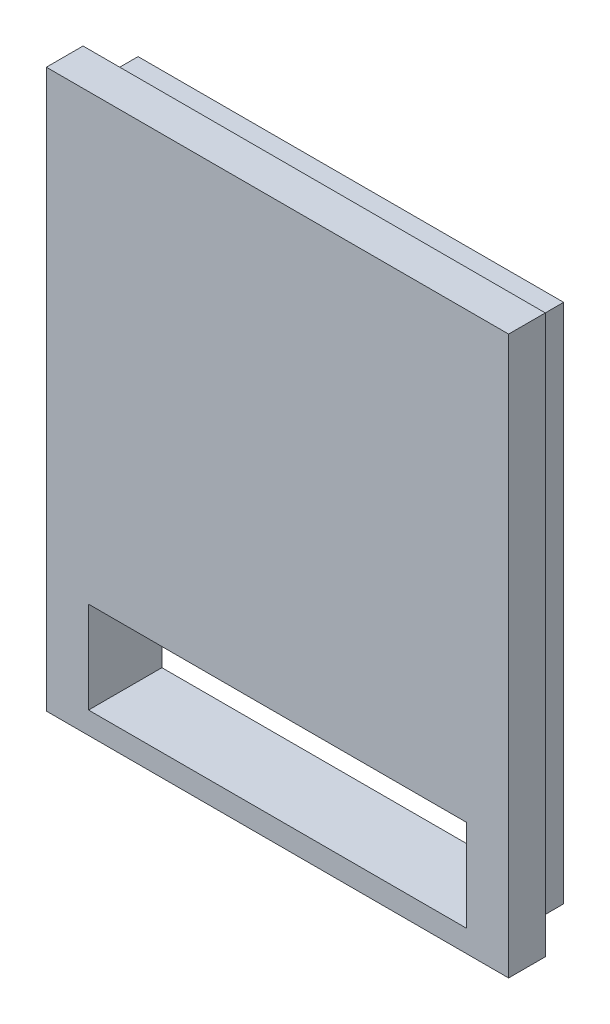
SolidWorks part; units mm, degrees
ref_plane "Front Plane" through (0, 0, 0) normal (0, 0, 1) x (1, 0, 0)
ref_plane "Top Plane" through (0, 0, 0) normal (0, 1, 0) x (1, 0, 0)
ref_plane "Right Plane" through (0, 0, 0) normal (1, 0, 0) x (0, 0, -1)
sketch "Sketch2" plane through (0, 0, 0) normal (0, 0, 1) x (1, 0, 0)
  line L1 (-6.3, -7.6) -> (6.3, -7.6)
  line L2 (-6.3, -7.6) -> (-6.3, 7.6)
  line L3 (-6.3, 7.6) -> (6.3, 7.6)
  line L4 (6.3, -7.6) -> (6.3, 7.6)
  line L5 (-6.3, -7.6) -> (6.3, 7.6) construction
  line L6 (-6.3, 7.6) -> (6.3, -7.6) construction
  point P0 (0, 0)
  dimension "D1" = 12.6
  dimension "D2" = 15.2
extrude "Boss-Extrude1" add sketch "Sketch2" along normal blind 1
sketch "Sketch3" plane through (0, 0, 0) normal (0, 0, -1) x (-1, 0, 0)
  line L1 (-5.8, -7.1) -> (5.8, -7.1)
  line L2 (-5.8, -7.1) -> (-5.8, 7.1)
  line L3 (-5.8, 7.1) -> (5.8, 7.1)
  line L4 (5.8, -7.1) -> (5.8, 7.1)
  line L5 (-5.8, -7.1) -> (5.8, 7.1) construction
  line L6 (-5.8, 7.1) -> (5.8, -7.1) construction
  point P0 (0, 0)
  dimension "D1" = 11.6
  dimension "D2" = 14.2
extrude "Boss-Extrude2" add sketch "Sketch3" along normal blind 1
sketch "Sketch4" plane through (0, 0, -1) normal (0, 0, -1) x (-1, 0, 0)
  line L0 (-5.8, -7.1) -> (5.8, -7.1) construction
  line L1 (-5.15, -4.5) -> (5.15, -4.5)
  line L2 (-5.15, -4.5) -> (-5.15, -7)
  line L3 (-5.15, -7) -> (5.15, -7)
  line L4 (5.15, -4.5) -> (5.15, -7)
  line L5 (-5.15, -4.5) -> (5.15, -7) construction
  line L6 (-5.15, -7) -> (5.15, -4.5) construction
  point P0 (0, -5.75)
  point P5 (0, -5.5219)
  point P6 (0, -5.4872)
  dimension "D1" = 2.5
  dimension "D2" = 10.3
  dimension "D3" = 0.1
extrude "Cut-Extrude1" cut sketch "Sketch4" against normal blind 4
